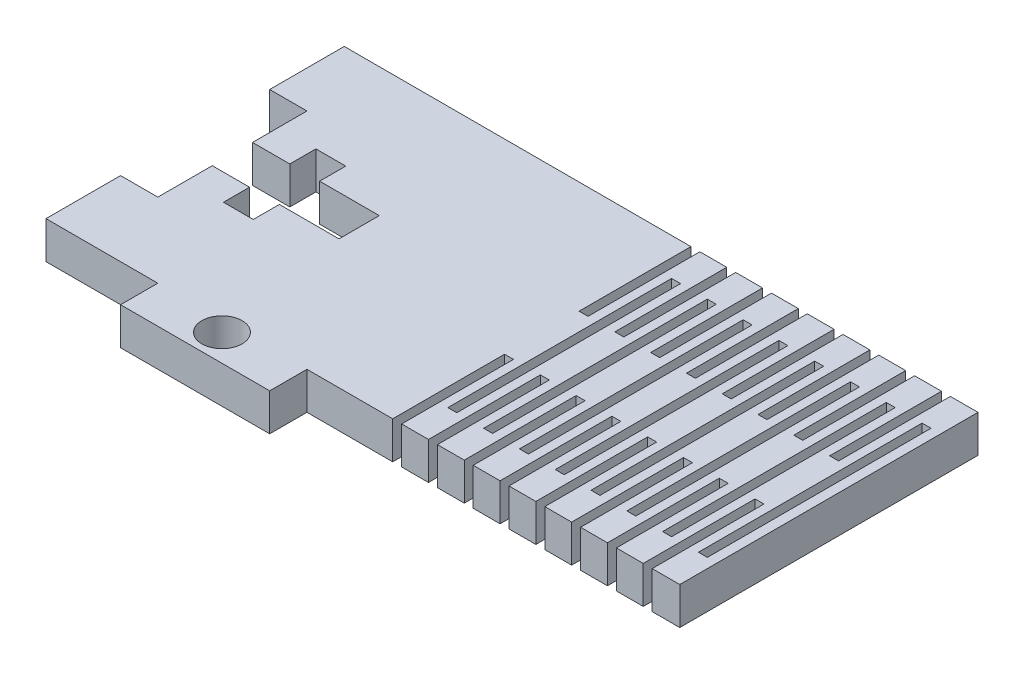
SolidWorks part; units mm, degrees
ref_plane "Front Plane" through (0, 0, 0) normal (0, 0, 1) x (1, 0, 0)
ref_plane "Top Plane" through (0, 0, 0) normal (0, 1, 0) x (1, 0, 0)
ref_plane "Right Plane" through (0, 0, 0) normal (1, 0, 0) x (0, 0, -1)
sketch "Sketch1" plane through (0, 0, 0) normal (0, 1, 0) x (1, 0, 0)
  line L0 (0, 19.05) -> (3.175, 19.05)
  line L1 (0, 0) -> (28.575, 0) construction
  line L2 (0, 0) -> (0, 6.35)
  line L3 (0, 25.4) -> (28.575, 25.4)
  line L4 (28.575, 0) -> (28.575, 25.4)
  line L5 (3.175, 19.05) -> (3.175, 6.35) construction
  line L6 (3.175, 6.35) -> (0, 6.35)
  line L7 (0, 0) -> (9.525, 0)
  line L8 (0, 19.05) -> (0, 25.4)
  line L9 (9.525, 0) -> (9.525, -3.175)
  line L10 (9.525, -3.175) -> (22.225, -3.175)
  line L11 (22.225, -3.175) -> (22.225, 0)
  line L12 (22.225, 0) -> (28.575, 0)
  line L13 (3.175, 12.7) -> (10.4775, 12.7) construction
  line L14 (3.175, 10.9855) -> (6.35, 10.9855)
  line L15 (6.35, 10.9855) -> (6.35, 8.763)
  line L16 (6.35, 8.763) -> (8.89, 8.763)
  line L17 (3.175, 6.35) -> (3.175, 10.9855)
  line L18 (8.89, 8.763) -> (8.89, 10.9855)
  line L19 (8.89, 10.9855) -> (13.97, 10.9855)
  line L20 (13.97, 10.9855) -> (13.97, 14.4145)
  line L21 (8.89, 14.4145) -> (13.97, 14.4145)
  line L22 (8.89, 16.637) -> (8.89, 14.4145)
  line L23 (6.35, 16.637) -> (8.89, 16.637)
  line L24 (6.35, 14.4145) -> (6.35, 16.637)
  line L25 (3.175, 14.4145) -> (6.35, 14.4145)
  line L26 (3.175, 19.05) -> (3.175, 14.4145)
  line L28 (15.875, -3.175) -> (15.875, -0.889) construction
  circle A0 centre (15.875, -0.889) radius 1.7145
  point P22 (13.97, 12.7)
  dimension "D11" = 3.429
  dimension "D1" = 28.575
  dimension "D2" = 25.4
  dimension "D3" = 3.175
  dimension "D4" = 12.7
  dimension "D5" = 6.35
  dimension "D6" = 2.54
  dimension "D8" = 2.286
  dimension "D9" = 3.937
  dimension "D10" = 1.7145
  dimension "D12" = 3.175
  dimension "D7" = 3.175
  dimension "D13" = 13.97
extrude "Boss-Extrude1" add sketch "Sketch1" along normal blind 3.175
sketch "Sketch3" plane through (28.575, 0, 0) normal (1, 0, 0) x (0, 0, -1)
  line L4 (0, 0) -> (25.4, 0)
  line L5 (25.4, 0) -> (25.4, 3.175)
  line L6 (25.4, 3.175) -> (0, 3.175)
  line L7 (0, 3.175) -> (0, 0)
  line L8 (0, 0) -> (25.4, 0)
  line L9 (25.4, 0) -> (25.4, 3.175)
  line L10 (25.4, 3.175) -> (0, 3.175)
  line L11 (0, 3.175) -> (0, 0)
  dimension "D1" = 0
extrude "Boss-Extrude2" add sketch "Sketch3" along normal blind 25.4
sketch "Sketch4" plane through (0, 3.175, 0) normal (0, 1, 0) x (1, 0, 0)
  line L0 (28.8923, 0) -> (28.8923, 25.4) construction
  line L1 (22.225, 0) -> (53.975, 0) construction
  line L2 (53.975, 25.4) -> (0, 25.4) construction
  line L3 (28.8923, 12.7) -> (53.975, 12.7) construction
  line L4 (53.975, 25.4) -> (53.975, 0) construction
  line L5 (29.5273, 0) -> (29.5273, 9.525)
  line L6 (29.5273, 9.525) -> (30.2893, 9.525)
  line L7 (30.2893, 9.525) -> (30.2893, 0)
  line L8 (31.0513, 22.225) -> (31.0513, 3.175)
  line L9 (31.0513, 3.175) -> (31.8133, 3.175)
  line L10 (31.8133, 3.175) -> (31.8133, 22.225)
  line L11 (29.5273, 0) -> (30.2893, 0)
  line L12 (29.5273, 25.4) -> (30.2893, 25.4)
  line L13 (31.0513, 22.225) -> (31.8133, 22.225)
  line L14 (30.2893, 15.875) -> (30.2893, 25.4)
  line L15 (29.5273, 15.875) -> (30.2893, 15.875)
  line L16 (29.5273, 25.4) -> (29.5273, 15.875)
  line L17 (32.5753, 0) -> (32.5753, 9.525)
  line L18 (32.5753, 9.525) -> (33.3373, 9.525)
  line L19 (33.3373, 9.525) -> (33.3373, 0)
  line L20 (34.0993, 22.225) -> (34.0993, 3.175)
  line L21 (34.0993, 3.175) -> (34.8613, 3.175)
  line L22 (34.8613, 3.175) -> (34.8613, 22.225)
  line L23 (32.5753, 0) -> (33.3373, 0)
  line L24 (32.5753, 25.4) -> (33.3373, 25.4)
  line L25 (34.0993, 22.225) -> (34.8613, 22.225)
  line L26 (33.3373, 15.875) -> (33.3373, 25.4)
  line L27 (32.5753, 15.875) -> (33.3373, 15.875)
  line L28 (32.5753, 25.4) -> (32.5753, 15.875)
  line L29 (35.6233, 0) -> (35.6233, 9.525)
  line L30 (35.6233, 9.525) -> (36.3853, 9.525)
  line L31 (36.3853, 9.525) -> (36.3853, 0)
  line L32 (37.1473, 22.225) -> (37.1473, 3.175)
  line L33 (37.1473, 3.175) -> (37.9093, 3.175)
  line L34 (37.9093, 3.175) -> (37.9093, 22.225)
  line L35 (35.6233, 0) -> (36.3853, 0)
  line L36 (35.6233, 25.4) -> (36.3853, 25.4)
  line L37 (37.1473, 22.225) -> (37.9093, 22.225)
  line L38 (36.3853, 15.875) -> (36.3853, 25.4)
  line L39 (35.6233, 15.875) -> (36.3853, 15.875)
  line L40 (35.6233, 25.4) -> (35.6233, 15.875)
  line L41 (38.6713, 0) -> (38.6713, 9.525)
  line L42 (38.6713, 9.525) -> (39.4333, 9.525)
  line L43 (39.4333, 9.525) -> (39.4333, 0)
  line L44 (40.1953, 22.225) -> (40.1953, 3.175)
  line L45 (40.1953, 3.175) -> (40.9573, 3.175)
  line L46 (40.9573, 3.175) -> (40.9573, 22.225)
  line L47 (38.6713, 0) -> (39.4333, 0)
  line L48 (38.6713, 25.4) -> (39.4333, 25.4)
  line L49 (40.1953, 22.225) -> (40.9573, 22.225)
  line L50 (39.4333, 15.875) -> (39.4333, 25.4)
  line L51 (38.6713, 15.875) -> (39.4333, 15.875)
  line L52 (38.6713, 25.4) -> (38.6713, 15.875)
  line L53 (41.7193, 0) -> (41.7193, 9.525)
  line L54 (41.7193, 9.525) -> (42.4813, 9.525)
  line L55 (42.4813, 9.525) -> (42.4813, 0)
  line L56 (43.2433, 22.225) -> (43.2433, 3.175)
  line L57 (43.2433, 3.175) -> (44.0053, 3.175)
  line L58 (44.0053, 3.175) -> (44.0053, 22.225)
  line L59 (41.7193, 0) -> (42.4813, 0)
  line L60 (41.7193, 25.4) -> (42.4813, 25.4)
  line L61 (43.2433, 22.225) -> (44.0053, 22.225)
  line L62 (42.4813, 15.875) -> (42.4813, 25.4)
  line L63 (41.7193, 15.875) -> (42.4813, 15.875)
  line L64 (41.7193, 25.4) -> (41.7193, 15.875)
  line L65 (44.7673, 0) -> (44.7673, 9.525)
  line L66 (44.7673, 9.525) -> (45.5293, 9.525)
  line L67 (45.5293, 9.525) -> (45.5293, 0)
  line L68 (46.2913, 22.225) -> (46.2913, 3.175)
  line L69 (46.2913, 3.175) -> (47.0533, 3.175)
  line L70 (47.0533, 3.175) -> (47.0533, 22.225)
  line L71 (44.7673, 0) -> (45.5293, 0)
  line L72 (44.7673, 25.4) -> (45.5293, 25.4)
  line L73 (46.2913, 22.225) -> (47.0533, 22.225)
  line L74 (45.5293, 15.875) -> (45.5293, 25.4)
  line L75 (44.7673, 15.875) -> (45.5293, 15.875)
  line L76 (44.7673, 25.4) -> (44.7673, 15.875)
  line L77 (47.8153, 0) -> (47.8153, 9.525)
  line L78 (47.8153, 9.525) -> (48.5773, 9.525)
  line L79 (48.5773, 9.525) -> (48.5773, 0)
  line L80 (49.3393, 22.225) -> (49.3393, 3.175)
  line L81 (49.3393, 3.175) -> (50.1013, 3.175)
  line L82 (50.1013, 3.175) -> (50.1013, 22.225)
  line L83 (47.8153, 0) -> (48.5773, 0)
  line L84 (47.8153, 25.4) -> (48.5773, 25.4)
  line L85 (49.3393, 22.225) -> (50.1013, 22.225)
  line L86 (48.5773, 15.875) -> (48.5773, 25.4)
  line L87 (47.8153, 15.875) -> (48.5773, 15.875)
  line L88 (47.8153, 25.4) -> (47.8153, 15.875)
  line L89 (50.8633, 0) -> (50.8633, 9.525)
  line L90 (50.8633, 9.525) -> (51.6253, 9.525)
  line L91 (51.6253, 9.525) -> (51.6253, 0)
  line L92 (52.3873, 22.225) -> (52.3873, 3.175)
  line L93 (52.3873, 3.175) -> (53.1493, 3.175)
  line L94 (53.1493, 3.175) -> (53.1493, 22.225)
  line L95 (50.8633, 0) -> (51.6253, 0)
  line L96 (50.8633, 25.4) -> (51.6253, 25.4)
  line L97 (52.3873, 22.225) -> (53.1493, 22.225)
  line L98 (51.6253, 15.875) -> (51.6253, 25.4)
  line L99 (50.8633, 15.875) -> (51.6253, 15.875)
  line L100 (50.8633, 25.4) -> (50.8633, 15.875)
  line L101 (31.0513, 12.7) -> (34.0993, 12.7) construction
  point P21 (31.8133, 12.7)
  point P22 (31.0513, 12.7)
  point P37 (34.8613, 12.7)
  point P38 (34.0993, 12.7)
  point P51 (37.9093, 12.7)
  point P52 (37.1473, 12.7)
  point P65 (40.9573, 12.7)
  point P66 (40.1953, 12.7)
  point P79 (44.0053, 12.7)
  point P80 (43.2433, 12.7)
  point P93 (47.0533, 12.7)
  point P94 (46.2913, 12.7)
  point P107 (50.1013, 12.7)
  point P108 (49.3393, 12.7)
  point P121 (53.1493, 12.7)
  point P122 (52.3873, 12.7)
  dimension "D1" = 0.762
  dimension "D2" = 3.175
  dimension "D3" = 1.27
  dimension "D4" = 0.762
  dimension "D5" = 8
  dimension "D6" = 3.048
extrude "Cut-Extrude2" cut sketch "Sketch4" against normal through all
